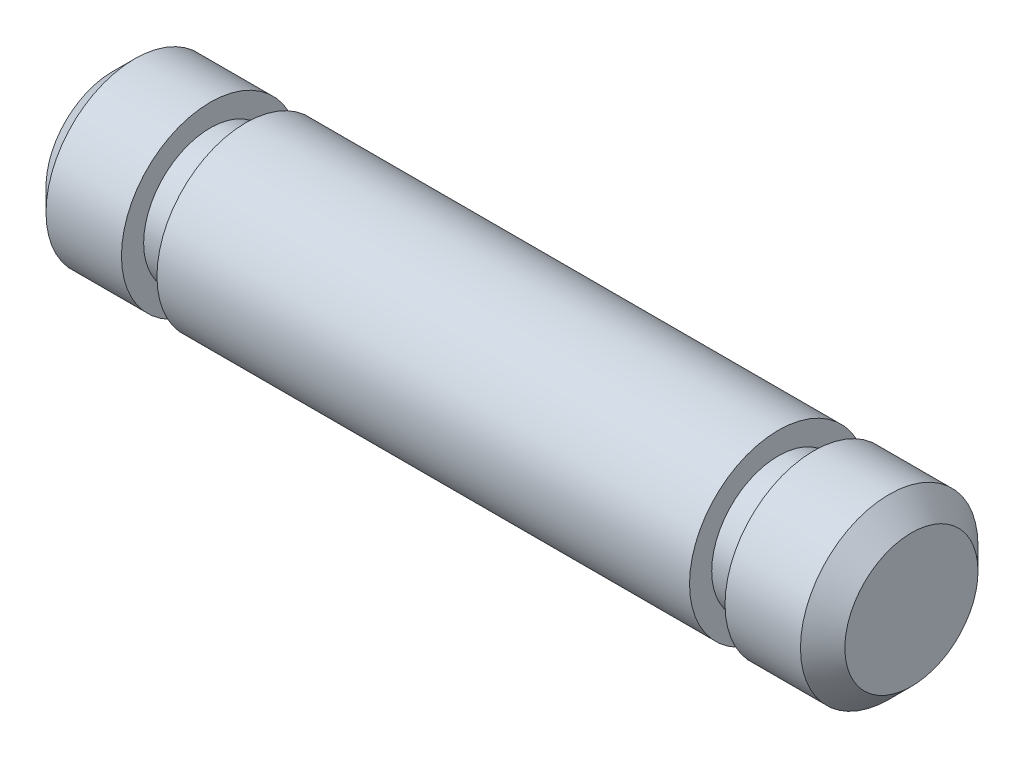
SolidWorks part; units mm, degrees
ref_plane "Front Plane" through (0, 0, 0) normal (0, 0, 1) x (1, 0, 0)
ref_plane "Top Plane" through (0, 0, 0) normal (0, 1, 0) x (1, 0, 0)
ref_plane "Right Plane" through (0, 0, 0) normal (1, 0, 0) x (0, 0, -1)
sketch "Sketch1" plane through (0, 0, 0) normal (1, 0, 0) x (0, 0, -1)
  circle A0 centre (0, 0) radius 2
  dimension "D1" = 4
extrude "Boss-Extrude1" add sketch "Sketch1" along normal mid plane 18
chamfer "Chamfer1" distance 0.5 angle 45 2 edges at (-9, 0, -2) (9, 0, -2)
sketch "Sketch2" plane through (-9, 0, 0) normal (-1, 0, 0) x (0, 0, 1)
  circle A0 centre (0, 0) radius 2 construction
  circle A1 centre (0, 0) radius 2
  circle A2 centre (0, 0) radius 1.5
  dimension "D1" = 3
extrude "Cut-Extrude1" cut sketch "Sketch2" along normal blind 0.8 from offset 3 offset against normal yes
mirror "Mirror1" about plane through (0, 0, 0) normal (1, 0, 0) of "Cut-Extrude1"
